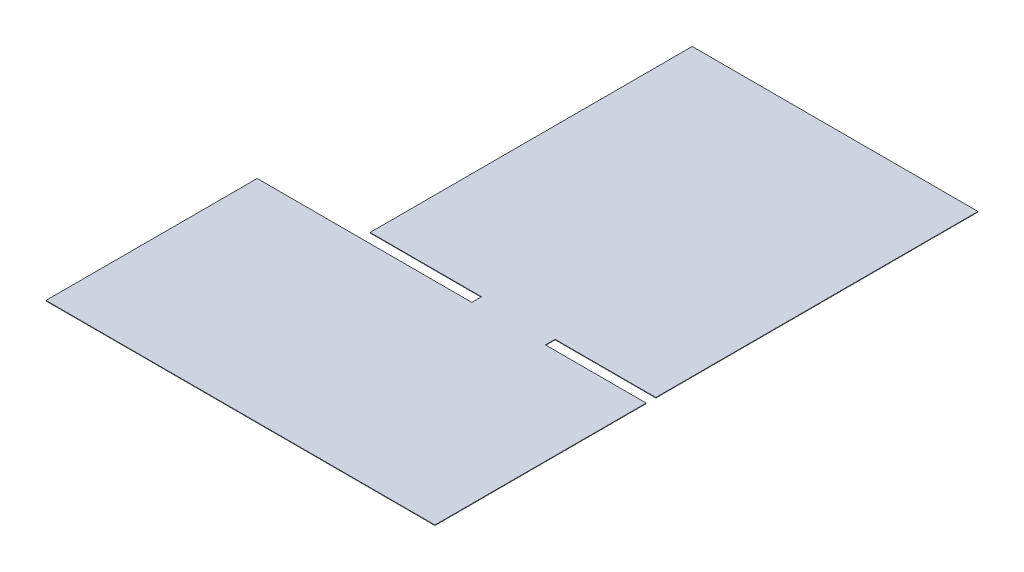
SolidWorks part; units mm, degrees
ref_plane "Front Plane" through (0, 0, 0) normal (0, 0, 1) x (1, 0, 0)
ref_plane "Top Plane" through (0, 0, 0) normal (0, 1, 0) x (1, 0, 0)
ref_plane "Right Plane" through (0, 0, 0) normal (1, 0, 0) x (0, 0, -1)
sketch "Sketch4" plane through (0, 0, 0) normal (0, 1, 0) x (1, 0, 0)
  line L0 (8030, 11210) -> (8030, 4560)
  line L1 (8030, 4560) -> (5950, 4560)
  line L2 (5950, 4560) -> (5950, 4360)
  line L3 (4430, 4360) -> (0, 4360)
  line L4 (0, 4360) -> (0, 0)
  line L5 (0, 0) -> (8030, 0)
  line L6 (4430, 4360) -> (4430, 4560)
  line L7 (8030, 0) -> (8030, 4360)
  line L8 (4430, 4560) -> (2130, 4560)
  line L9 (2130, 4560) -> (2130, 11210)
  line L10 (5950, 4360) -> (8030, 4360)
  line L11 (2130, 11210) -> (8030, 11210)
  dimension "D1" = 6650
  dimension "D2" = 5900
  dimension "D3" = 2080
  dimension "D4" = 2300
  dimension "D6" = 4430
  dimension "D7" = 2080
  dimension "D8" = 6650
  dimension "D9" = 4360
  dimension "D10" = 4360
  dimension "D11" = 200
extrude "Boss-Extrude1" add sketch "Sketch4" along normal blind 10
